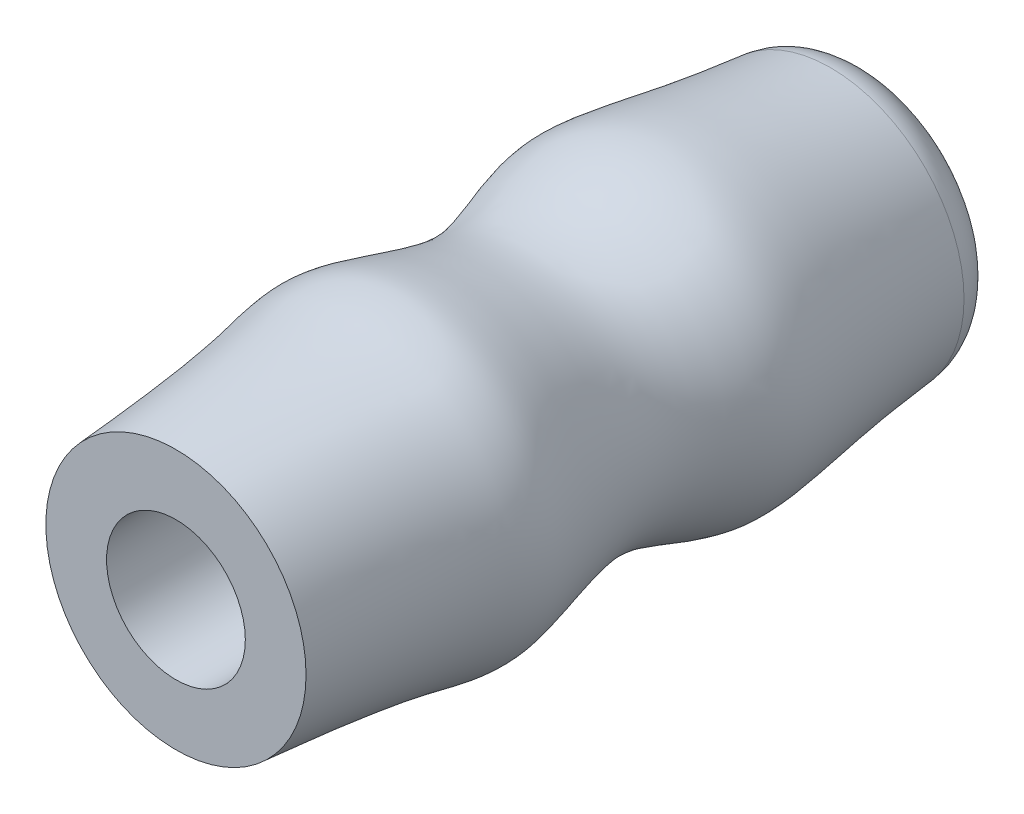
SolidWorks part; units mm, degrees
ref_plane "Front Plane" through (0, 0, 0) normal (0, 0, 1) x (1, 0, 0)
ref_plane "Top Plane" through (0, 0, 0) normal (0, 1, 0) x (1, 0, 0)
ref_plane "Right Plane" through (0, 0, 0) normal (1, 0, 0) x (0, 0, -1)
sketch "Esboço1" plane through (0, 0, 0) normal (0, 1, 0) x (1, 0, 0)
  line L0 (0, -35.1159) -> (0, 46.4735) construction
  line L1 (-8, -35.1159) -> (-8, 34.8841)
  line L2 (-15, -35.1159) -> (-15, 44.8841) construction
  line L3 (-15, -35.1159) -> (-8, -35.1159)
  line L4 (-8, 34.8841) -> (0, 34.8841)
  line L5 (0, 34.8841) -> (0, 44.8841)
  line L6 (0, 44.8841) -> (-15, 44.8841)
  spline S0 degree 3 poles (-15, -35.1159) (-16.4374, -16.1971) (-17.7674, -15.3288) (-18.2076, -6.6302) (-12.4358, 6.8059) (-20.5222, 17.9357) (-16.0805, 29.6088) (-15, 44.8841) knots 0 0 0 0 0.27115 0.323134 0.519842 0.746213 1 1 1 1
  point P7 (0, 0)
  dimension "D5" = 10
  dimension "D1" = 70
  dimension "D2" = 8
  dimension "D3" = 80
  dimension "D4" = 15
  dimension "D6" = 10
  dimension "D7" = 25
  dimension "D8" = 25
revolve "Revolução1" add sketch "Esboço1" angle 360 about L0
fillet "Filete1" radius 5 1 edges at (15, 0, -44.8841)
sketch "Esboço3" plane through (0, 0, 0) normal (0, 1, 0) x (1, 0, 0)
  spline S0 degree 3 poles (-15.3774, 40.3655) (-15.3779, 40.3601) (-15.4679, 39.4299) (-15.6114, 38.0658) (-15.824, 36.2627) (-15.9891, 34.9542) (-16.1568, 33.7042) (-16.323, 32.5286) (-16.4794, 31.4683) (-16.6324, 30.4656) (-16.7791, 29.5285) (-16.9204, 28.6429) (-17.0543, 27.8122) (-17.1793, 27.0381) (-17.2995, 26.2882) (-17.4116, 25.5768) (-17.5136, 24.9101) (-17.6084, 24.2654) (-17.6915, 23.6667) (-17.7651, 23.0957) (-17.8311, 22.5351) (-17.892, 21.9446) (-17.9439, 21.3241) (-17.9804, 20.7183) (-17.9997, 20.1389) (-18.0019, 19.5897) (-17.9871, 19.0574) (-17.9613, 18.6456) (-17.9287, 18.276) (-17.886, 17.8882) (-17.8154, 17.4039) (-17.7215, 16.8858) (-17.6115, 16.3665) (-17.4772, 15.8132) (-17.3162, 15.2203) (-17.1222, 14.5652) (-16.9043, 13.8801) (-16.6626, 13.1509) (-16.4202, 12.4314) (-16.1903, 11.7402) (-15.9924, 11.124) (-15.8165, 10.5492) (-15.6569, 9.9923) (-15.51, 9.4325) (-15.3827, 8.8943) (-15.2731, 8.366) (-15.1824, 7.8532) (-15.1107, 7.3621) (-15.0527, 6.8544) (-15.0104, 6.3243) (-14.9874, 5.7639) (-14.9868, 5.2916) (-14.9999, 4.8428) (-15.0224, 4.4506) (-15.0631, 3.9757) (-15.1178, 3.4909) (-15.1932, 2.9512) (-15.2854, 2.3901) (-15.3916, 1.8228) (-15.5088, 1.2551) (-15.6476, 0.6324) (-15.8195, -0.0847) (-16.0397, -0.9465) (-16.2815, -1.8469) (-16.517, -2.6996) (-16.722, -3.4374) (-16.9006, -4.0838) (-17.0631, -4.6821) (-17.2079, -5.2296) (-17.335, -5.7265) (-17.447, -6.1838) (-17.5505, -6.628) (-17.641, -7.0422) (-17.721, -7.4385) (-17.7874, -7.7974) (-17.8458, -8.1499) (-17.8941, -8.485) (-17.9264, -8.7532) (-17.9608, -9.0914) (-17.9865, -9.454) (-18.0002, -9.8896) (-18.0007, -10.2581) (-17.9916, -10.5982) (-17.9762, -10.9077) (-17.9572, -11.1841) (-17.9386, -11.4059) (-17.9182, -11.6241) (-17.8923, -11.8767) (-17.8564, -12.1821) (-17.8134, -12.504) (-17.7674, -12.8146) (-17.7126, -13.152) (-17.6428, -13.5487) (-17.5648, -13.9614) (-17.483, -14.3789) (-17.4062, -14.7656) (-17.3279, -15.1601) (-17.2457, -15.5795) (-17.1603, -16.0253) (-17.0644, -16.5417) (-16.9523, -17.1705) (-16.784, -18.1671) (-16.6143, -19.2707) (-16.4448, -20.4724) (-16.307, -21.516) (-16.1672, -22.6456) (-16.0253, -23.8647) (-15.879, -25.2021) (-15.7282, -26.6711) (-15.5757, -28.2492) (-15.4216, -29.9427) (-15.263, -31.79) (-15.1371, -33.3438) (-15.056, -34.3845) (-15.0248, -34.7913) (-15.0106, -34.9763) (-15.0035, -35.0693) (-15, -35.1159) knots 0 0 0 0 0.00021 0.036608 0.05373 0.071331 0.088268 0.103135 0.117842 0.130251 0.142869 0.154996 0.165379 0.175832 0.18571 0.195129 0.204044 0.212128 0.220657 0.227719 0.234682 0.242769 0.250971 0.259073 0.266541 0.273678 0.280584 0.287396 0.289839 0.295118 0.302678 0.309006 0.315743 0.323466 0.331309 0.339808 0.350228 0.35947 0.369899 0.379971 0.388003 0.395252 0.403517 0.410695 0.417922 0.425179 0.431827 0.438318 0.444619 0.451844 0.459145 0.466585 0.470341 0.476732 0.481971 0.489012 0.495839 0.503319 0.511284 0.518444 0.526026 0.536276 0.547327 0.560871 0.572795 0.58198 0.590867 0.599065 0.606264 0.613053 0.619157 0.624708 0.630917 0.635764 0.640548 0.645214 0.649757 0.653809 0.655795 0.663075 0.668042 0.672866 0.67751 0.681365 0.685007 0.688363 0.690082 0.69359 0.698311 0.702126 0.706314 0.710607 0.715516 0.722093 0.727062 0.732181 0.737535 0.742816 0.748922 0.755319 0.76339 0.773942 0.794908 0.807126 0.821482 0.836142 0.851713 0.869561 0.888842 0.909558 0.931667 0.955455 0.982188 0.992731 0.996348 0.99817 1 1 1 1 construction
  point P0 (-15, -35.1159)
  point P1 (-17.9982, -9.8828)
  point P3 (-15.0002, 6.0537)
  point P6 (-17.9976, 20.1035)
  point P7 (-15.4091, 40.0405)
